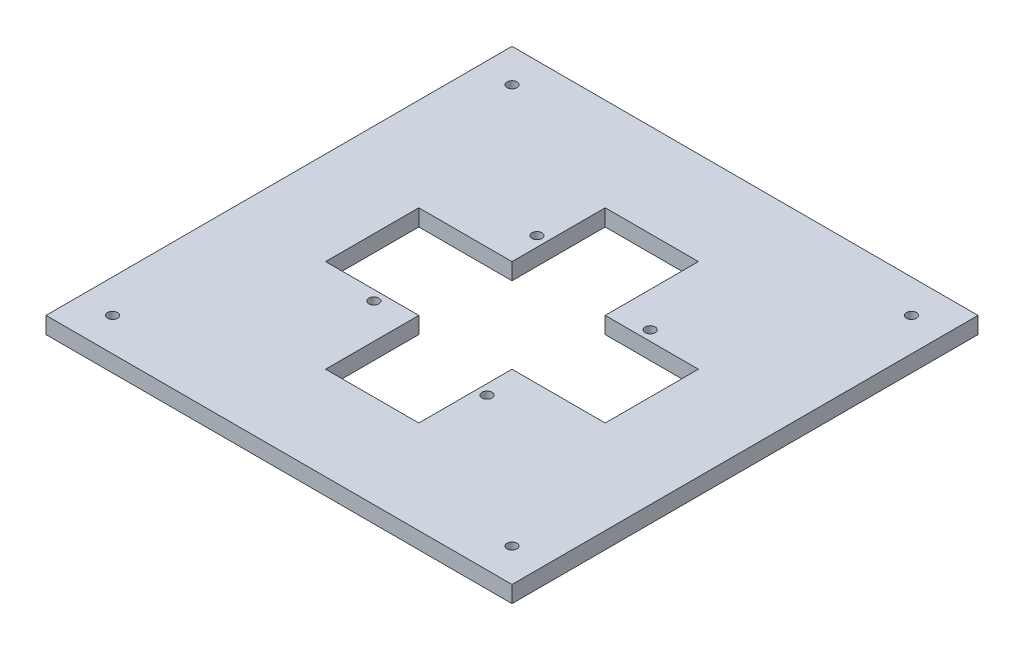
SolidWorks part; units mm, degrees
ref_plane "Front Plane" through (0, 0, 0) normal (0, 0, 1) x (1, 0, 0)
ref_plane "Top Plane" through (0, 0, 0) normal (0, 1, 0) x (1, 0, 0)
ref_plane "Right Plane" through (0, 0, 0) normal (1, 0, 0) x (0, 0, -1)
sketch "Sketch1" plane through (0, 0, 0) normal (0, 1, 0) x (1, 0, 0)
  line L1 (-70, 70) -> (70, 70)
  line L2 (-70, 70) -> (-70, -70)
  line L3 (-70, -70) -> (70, -70)
  line L4 (70, 70) -> (70, -70)
  line L5 (-70, 70) -> (70, -70) construction
  line L6 (-70, -70) -> (70, 70) construction
  point P0 (0, 0)
  dimension "D1" = 140
extrude "Boss-Extrude1" add sketch "Sketch1" along normal blind 5
sketch "Sketch2" plane through (0, 0, 0) normal (0, -1, 0) x (1, 0, 0)
  circle A0 centre (24.505, -17.005) radius 1.5
  circle A1 centre (-17.005, -24.505) radius 1.5
  circle A2 centre (-24.505, 17.005) radius 1.5
  circle A3 centre (17.005, 24.505) radius 1.5
  dimension "D1" = 3
  dimension "D2" = 3
  dimension "D3" = 3
  dimension "D4" = 3
extrude "Cut-Extrude1" cut sketch "Sketch2" against normal up to surface (5 mm away) up to face at (0, 5, 0)
sketch "Sketch4" plane through (0, 5, 0) normal (0, 1, 0) x (1, 0, 0)
  line L0 (0, 70) -> (0, 42) construction
  line L1 (70, 70) -> (-70, 70) construction
  line L2 (-14, 42) -> (14, 42)
  line L3 (14, 42) -> (14, 14)
  line L4 (-14, 42) -> (-14, 14)
  line L7 (14, 14) -> (42, 14)
  line L8 (-42, 14) -> (-14, 14)
  line L9 (42, 14) -> (42, -14)
  line L10 (42, -14) -> (14, -14)
  line L11 (14, -14) -> (14, -42)
  line L12 (14, -42) -> (-14, -42)
  line L13 (-14, -42) -> (-14, -14)
  line L14 (-14, -14) -> (-42, -14)
  line L15 (-42, -14) -> (-42, 14)
  point P8 (0, 42)
  point P17 (-42, 0)
  dimension "D1" = 28
  dimension "D2" = 14
  dimension "D3" = 42
  dimension "D4" = 14
  dimension "D5" = 14
  dimension "D6" = 28
  dimension "D7" = 28
  dimension "D8" = 28
  dimension "D9" = 42
  dimension "D10" = 14
  dimension "D11" = 42
extrude "Cut-Extrude2" cut sketch "Sketch4" against normal up to surface (5 mm away) up to face at (24.505, 0, -18.505)
sketch "Sketch6" plane through (0, 5, 0) normal (0, 1, 0) x (1, 0, 0)
  circle A0 centre (-60, 60) radius 1.5
  circle A1 centre (60, 60) radius 1.5
  circle A2 centre (60, -60) radius 1.5
  circle A3 centre (-60, -60) radius 1.5
  dimension "D1" = 3
extrude "Cut-Extrude4" cut sketch "Sketch6" against normal up to surface (5 mm away) up to face at (0, 0, 0)
